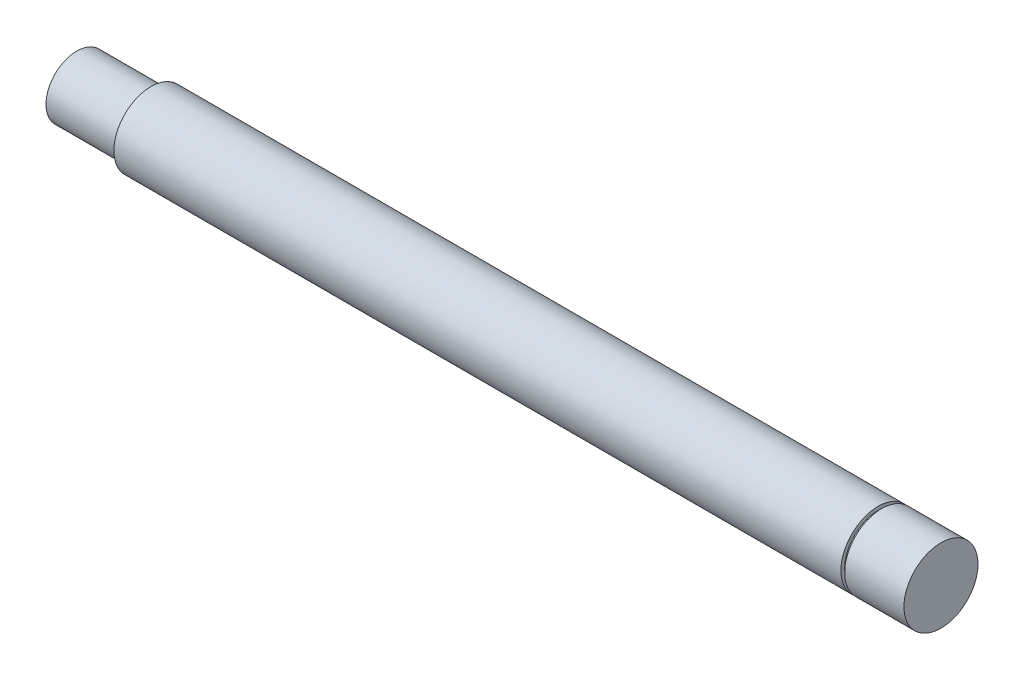
SolidWorks part; units mm, degrees
material "PW20:29:Sc:0:"
ref_plane "Front" through (0, 0, 0) normal (0, 0, 1) x (1, 0, 0)
ref_plane "Top" through (0, 0, 0) normal (0, 1, 0) x (1, 0, 0)
ref_plane "Right" through (0, 0, 0) normal (1, 0, 0) x (0, 0, -1)
sketch "Sketch1" plane through (0, 0, 0) normal (1, 0, 0) x (0, 0, -1)
  circle A0 centre (0, 0) radius 7.5
  dimension "D1" = 15
extrude "Base-Extrude" add sketch "Sketch1" along normal blind 175
ref_plane "Plane4" through (163, 0, 0) normal (1, 0, 0) x (0, 0, -1)
sketch "Sketch2" plane through (163, 0, 0) normal (1, 0, 0) x (0, 0, -1)
  circle A1 centre (0, 0) radius 6.75
  circle A2 centre (0, 0) radius 6.75
  circle A3 centre (0, 0) radius 7.5
  circle A4 centre (0, 0) radius 7.5
  dimension "D1" = 0.75
  dimension "D2" = 0
extrude "Cut-Extrude1" cut sketch "Sketch2" against normal blind 0.75
sketch "Sketch3" plane through (0, 0, 0) normal (-1, 0, 0) x (0, 0, 1)
  circle A0 centre (0, 0) radius 7.5 construction
  circle A1 centre (0, 0) radius 6.25
  circle A2 centre (0, 0) radius 6.25
  circle A3 centre (0, 0) radius 7.5
  dimension "D1" = 1.25
extrude "Cut-Extrude2" cut sketch "Sketch3" against normal blind 15
